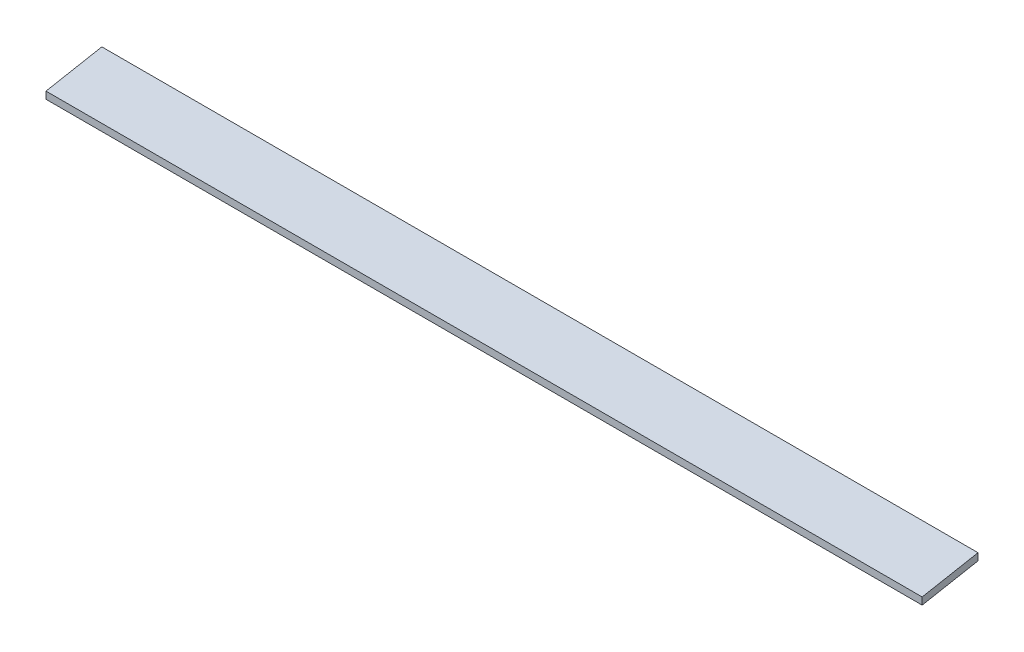
SolidWorks part; units mm, degrees
ref_plane "Спереди" through (0, 0, 0) normal (0, 0, 1) x (1, 0, 0)
ref_plane "Сверху" through (0, 0, 0) normal (0, 1, 0) x (1, 0, 0)
ref_plane "Справа" through (0, 0, 0) normal (1, 0, 0) x (0, 0, -1)
sketch "Эскиз1" plane through (0, 0, 0) normal (1, 0, 0) x (0, 0, -1)
  line L0 (337.9919, 112.5167) -> (-55.2385, 39.2376)
  line L1 (-55.2385, 39.2376) -> (-55.2385, -10.7624)
  line L2 (-55.2385, -10.7624) -> (337.9919, 62.5167)
  line L3 (337.9919, 62.5167) -> (337.9919, 112.5167)
extrude "Бобышка-Вытянуть1" add sketch "Эскиз1" along normal blind 6170
